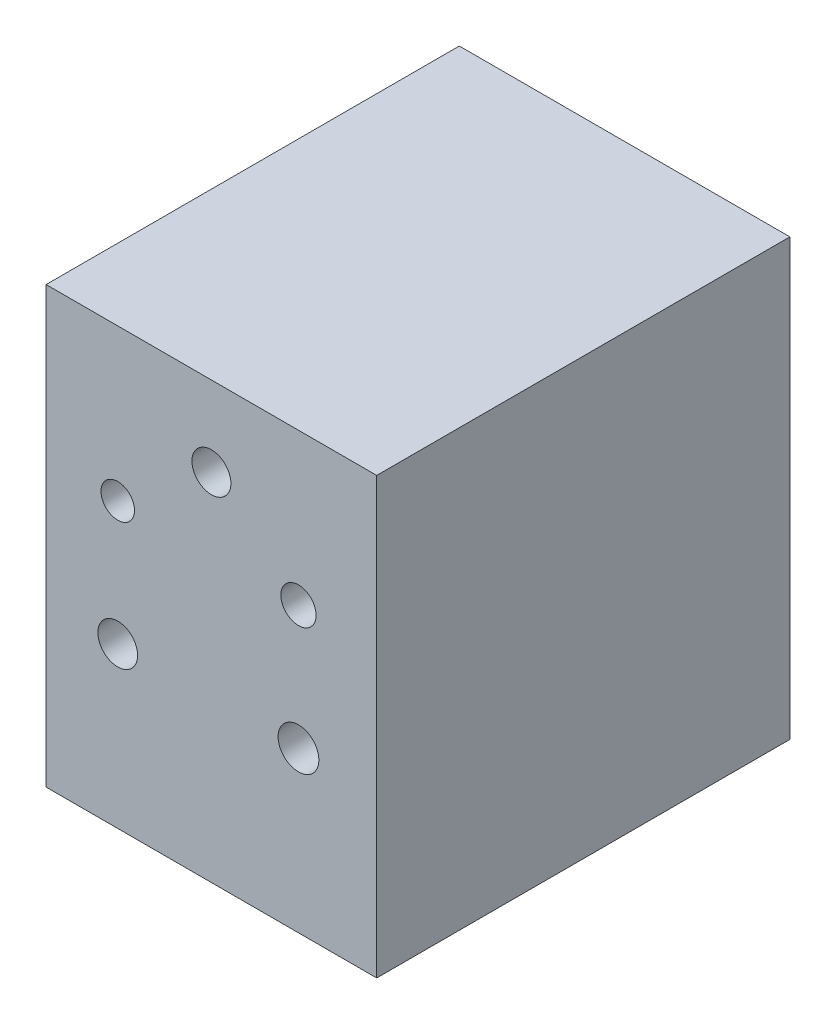
SolidWorks part; units mm, degrees
ref_plane "Front Plane" through (0, 0, 0) normal (0, 0, 1) x (1, 0, 0)
ref_plane "Top Plane" through (0, 0, 0) normal (0, 1, 0) x (1, 0, 0)
ref_plane "Right Plane" through (0, 0, 0) normal (1, 0, 0) x (0, 0, -1)
sketch "Sketch3" plane through (0, 0, 0) normal (0, 0, 1) x (1, 0, 0)
  line L1 (27.9874, -24.9203) -> (120.0006, -24.9203)
  line L2 (27.9874, -24.9203) -> (27.9874, 96.2306)
  line L3 (27.9874, 96.2306) -> (120.0006, 96.2306)
  line L4 (120.0006, -24.9203) -> (120.0006, 96.2306)
  line L5 (27.9874, -24.9203) -> (120.0006, 96.2306) construction
  line L6 (27.9874, 96.2306) -> (120.0006, -24.9203) construction
  circle A0 centre (73.994, 73.994) radius 5.4219
  circle A1 centre (47.9236, 54.0578) radius 4.6641
  circle A2 centre (98.2242, 54.0578) radius 4.9074
  circle A3 centre (47.9236, 19.5528) radius 5.5293
  circle A4 centre (98.2242, 19.5528) radius 5.6741
  point P0 (73.994, 35.6552)
extrude "Boss-Extrude2" add sketch "Sketch3" along normal blind 115
